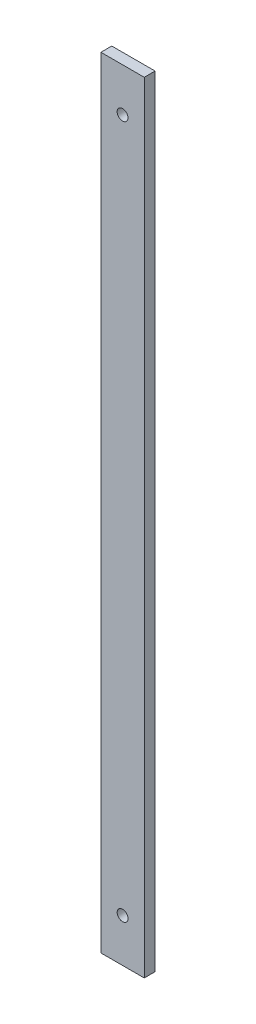
SolidWorks part; units mm, degrees
ref_plane "Front Plane" through (0, 0, 0) normal (0, 0, 1) x (1, 0, 0)
ref_plane "Top Plane" through (0, 0, 0) normal (0, 1, 0) x (1, 0, 0)
ref_plane "Right Plane" through (0, 0, 0) normal (1, 0, 0) x (0, 0, -1)
sketch "Sketch1" plane through (0, 0, 0) normal (0, 0, 1) x (1, 0, 0)
  line L0 (55, 0) -> (-55, 0) construction
  line L1 (-50.8, 0) -> (50.8, 0)
  line L2 (-50.8, 0) -> (-50.8, 1828.8)
  line L3 (-50.8, 1828.8) -> (50.8, 1828.8)
  line L4 (50.8, 0) -> (50.8, 1828.8)
  point P6 (0, 0)
  dimension "D1" = 101.6
  dimension "D2" = 1828.8
extrude "Boss-Extrude1" add sketch "Sketch1" along normal blind 25.4
sketch "Sketch2" plane through (0, 0, 25.4) normal (0, 0, 1) x (1, 0, 0)
  line L0 (0, 1828.8) -> (0, 0) construction
  line L1 (50.8, 1828.8) -> (-50.8, 1828.8) construction
  line L2 (-50.8, 0) -> (50.8, 0) construction
  circle A0 centre (0, 1727.2) radius 12.7
  circle A1 centre (0, 101.6) radius 12.7
  dimension "D1" = 25.4
  dimension "D3" = 25.4
  dimension "D2" = 101.6
  dimension "D4" = 101.6
extrude "Cut-Extrude1" cut sketch "Sketch2" against normal through all
